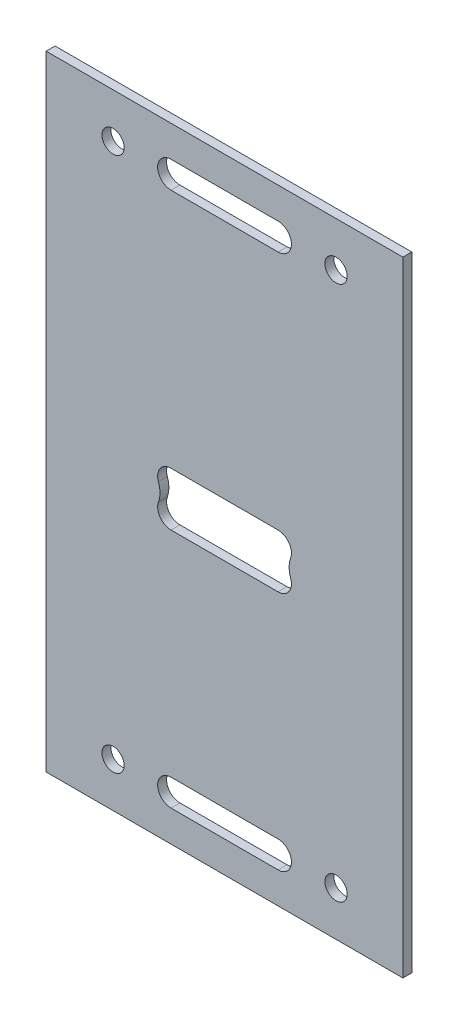
SolidWorks part; units mm, degrees
ref_plane "Front Plane" through (0, 0, 0) normal (0, 0, 1) x (1, 0, 0)
ref_plane "Top Plane" through (0, 0, 0) normal (0, 1, 0) x (1, 0, 0)
ref_plane "Right Plane" through (0, 0, 0) normal (1, 0, 0) x (0, 0, -1)
sketch "Sketch1" plane through (0, 0, 0) normal (0, 0, 1) x (1, 0, 0)
  line L0 (12.5, 30) -> (-12.5, -30) construction
  line L1 (-20, -35) -> (20, -35)
  line L2 (-20, -35) -> (-20, 35)
  line L3 (-20, 35) -> (20, 35)
  line L4 (20, -35) -> (20, 35)
  line L5 (-20, -35) -> (20, 35) construction
  line L6 (-20, 35) -> (20, -35) construction
  circle A0 centre (-12.5, 30) radius 1.25
  circle A1 centre (12.5, 30) radius 1.25
  circle A2 centre (-12.5, -30) radius 1.25
  circle A3 centre (12.5, -30) radius 1.25
  point P0 (0, 0)
  point P14 (0, 0)
  dimension "D3" = 2.5
  dimension "D1" = 25
  dimension "D2" = 60
  dimension "D4" = 70
  dimension "D5" = 40
extrude "Boss-Extrude1" add sketch "Sketch1" along normal blind 1
sketch "Sketch2" plane through (0, 0, 1) normal (0, 0, 1) x (1, 0, 0)
  line L0 (-6, 30) -> (6, 30) construction
  line L1 (-6, 31.5) -> (6, 31.5)
  line L2 (-6, 28.5) -> (6, 28.5)
  line L3 (-6, 0) -> (6, 0) construction
  line L4 (-6, 1.5) -> (6, 1.5)
  line L6 (-12.5, -30) -> (-6, -30) construction
  line L9 (-6, -30) -> (6, -30) construction
  line L10 (-6, -28.5) -> (6, -28.5)
  line L11 (-6, -31.5) -> (6, -31.5)
  line L12 (-6, -3) -> (6, -3) construction
  line L14 (-6, -4.5) -> (6, -4.5)
  line L15 (-6, -1.5) -> (6, -1.5) construction
  arc A0 (-6, 31.5) -> (-6, 28.5) centre (-6, 30) ccw
  arc A1 (6, 28.5) -> (6, 31.5) centre (6, 30) ccw
  arc A2 (-6, 1.5) -> (-6, -1.5) centre (-6, 0) ccw
  arc A3 (6, -1.5) -> (6, 1.5) centre (6, 0) ccw
  arc A6 (-6, -28.5) -> (-6, -31.5) centre (-6, -30) ccw
  arc A7 (6, -31.5) -> (6, -28.5) centre (6, -30) ccw
  arc A9 (-6, -1.5) -> (-6, -4.5) centre (-6, -3) ccw
  arc A10 (6, -4.5) -> (6, -1.5) centre (6, -3) ccw
  point P2 (0, 30)
  point P8 (0, 0)
  point P17 (0, -3)
  point P23 (0, -30)
  dimension "D2" = 1.5
  dimension "D6" = 1.5
  dimension "D1" = 12
  dimension "D3" = 30
  dimension "D4" = 30
extrude "Cut-Extrude1" cut sketch "Sketch2" against normal through all
fillet "Fillet1" radius 3 2 edges at (6, -1.5, 0.5) (-6, -1.5, 0.5)
